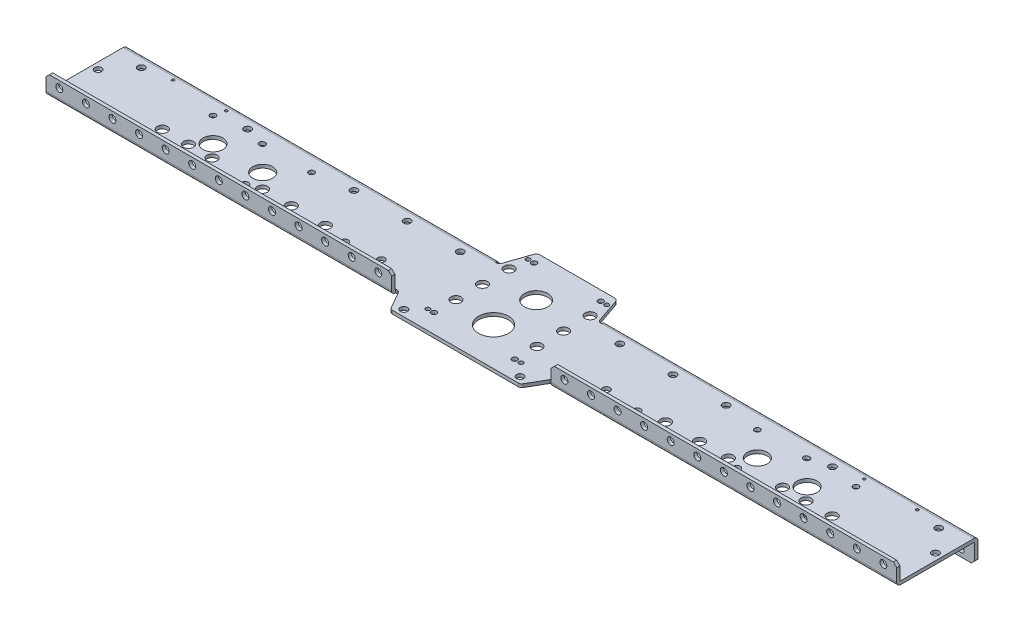
SolidWorks part; units mm, degrees
ref_plane "Front Plane" through (0, 0, 0) normal (0, 0, 1) x (1, 0, 0)
ref_plane "Top Plane" through (0, 0, 0) normal (0, 1, 0) x (1, 0, 0)
ref_plane "Right Plane" through (0, 0, 0) normal (1, 0, 0) x (0, 0, -1)
sketch "Sketch1" plane through (0, 0, 0) normal (0, 1, 0) x (1, 0, 0)
  line L32 (442.3147, 97.282) -> (370.4853, 97.282)
  line L33 (367.4833, 95.1407) -> (359.5123, 71.9913)
  line L34 (356.5103, 69.85) -> (355.6, 69.85)
  line L35 (355.6, 69.85) -> (0, 69.85)
  line L36 (0, 69.85) -> (0, 0)
  line L37 (0, 0) -> (330.2, 0)
  line L38 (330.2, 0) -> (331.5419, 0)
  line L39 (334.2915, -1.5875) -> (343.457, -17.4625)
  line L40 (346.2066, -19.05) -> (466.5934, -19.05)
  line L41 (469.343, -17.4625) -> (478.5085, -1.5875)
  line L42 (481.2581, 0) -> (482.6, 0)
  line L43 (482.6, 0) -> (812.8, 0)
  line L44 (812.8, 0) -> (812.8, 69.85)
  line L45 (812.8, 69.85) -> (457.2, 69.85)
  line L46 (457.2, 69.85) -> (456.2897, 69.85)
  line L47 (453.2877, 71.9913) -> (445.3167, 95.1407)
  circle A1 centre (806.45, 39.497) radius 3.3528
  arc A16 (445.3167, 95.1407) -> (442.3147, 97.282) centre (442.3147, 94.107) ccw
  arc A17 (370.4853, 97.282) -> (367.4833, 95.1407) centre (370.4853, 94.107) ccw
  arc A18 (356.5103, 69.85) -> (359.5123, 71.9913) centre (356.5103, 73.025) ccw
  arc A19 (334.2915, -1.5875) -> (331.5419, 0) centre (331.5419, -3.175) ccw
  arc A20 (343.457, -17.4625) -> (346.2066, -19.05) centre (346.2066, -15.875) ccw
  arc A21 (466.5934, -19.05) -> (469.343, -17.4625) centre (466.5934, -15.875) ccw
  arc A22 (481.2581, 0) -> (478.5085, -1.5875) centre (481.2581, -3.175) ccw
  arc A23 (453.2877, 71.9913) -> (456.2897, 69.85) centre (456.2897, 73.025) ccw
  circle A34 centre (641.35, 14.732) radius 3.3528
  circle A35 centre (642.7129, 33.02) radius 9.525
  arc A36 (666.4551, 53.7309) -> (666.4551, 59.0065) centre (666.8486, 56.3687) ccw
  arc A37 (666.4551, 7.0335) -> (666.4551, 12.3091) centre (666.8486, 9.6713) ccw
  circle A38 centre (678.9442, 20.828) radius 4.826
  circle A39 centre (711.2, 3.175) radius 1.27
  circle A40 centre (713.546, 9.6713) radius 2.667
  circle A41 centre (701.4504, 20.828) radius 4.826
  circle A42 centre (690.1973, 33.02) radius 9.525
  circle A43 centre (685.8, 61.722) radius 3.3528
  circle A44 centre (711.2, 66.675) radius 1.27
  circle A45 centre (713.546, 56.3687) radius 2.667
  circle A46 centre (726.4609, 20.828) radius 4.826
  circle A47 centre (762, 3.175) radius 1.27
  circle A48 centre (762, 66.675) radius 1.27
  circle A49 centre (787.4, 61.722) radius 3.3528
  circle A78 centre (350.8375, -12.8905) radius 3.4036
  circle A79 centre (361.9119, -1.0389) radius 2.032
  circle A80 centre (367.7539, -1.0389) radius 2.54
  circle A81 centre (367.6757, 20.066) radius 4.7625
  circle A82 centre (367.6757, 45.466) radius 4.7625
  circle A83 centre (367.6757, 70.866) radius 4.7625
  circle A84 centre (368.808, 87.8535) radius 2.032
  circle A85 centre (374.65, 87.8535) radius 2.54
  circle A86 centre (406.4, 57.9628) radius 11.1125
  circle A87 centre (406.4, 17.272) radius 14.2875
  circle A88 centre (461.9625, -12.8905) radius 3.4036
  circle A89 centre (445.0461, -1.0389) radius 2.54
  circle A90 centre (450.8881, -1.0389) radius 2.032
  circle A91 centre (445.1243, 20.066) radius 4.7625
  circle A92 centre (445.1243, 45.466) radius 4.7625
  circle A93 centre (438.15, 87.8535) radius 2.54
  circle A94 centre (443.992, 87.8535) radius 2.032
  circle A95 centre (445.1243, 70.866) radius 4.7625
  circle A96 centre (482.6, 61.722) radius 3.3528
  circle A97 centre (513.9255, 17.5473) radius 3.3528
  circle A98 centre (533.4, 61.722) radius 3.3528
  circle A99 centre (546.1, 14.732) radius 3.3528
  circle A100 centre (568.9249, 19.05) radius 4.826
  circle A101 centre (584.2, 61.722) radius 3.3528
  circle A102 centre (619.3642, 56.3687) radius 2.667
  circle A103 centre (601.4385, 19.05) radius 4.826
  circle A104 centre (619.3642, 9.6713) radius 2.667
  circle A105 centre (628.9477, 19.05) radius 4.826
  circle A125 centre (298.8745, 17.5473) radius 3.3528
  circle A126 centre (266.7, 14.732) radius 3.3528
  circle A127 centre (243.8751, 19.05) radius 4.826
  circle A128 centre (211.3615, 19.05) radius 4.826
  circle A129 centre (193.4358, 9.6713) radius 2.667
  circle A130 centre (183.8523, 19.05) radius 4.826
  circle A131 centre (170.0871, 33.02) radius 9.525
  circle A132 centre (171.45, 14.732) radius 3.3528
  arc A133 (146.3449, 7.0335) -> (146.3449, 12.3091) centre (146.7384, 9.6713) ccw
  circle A134 centre (133.8558, 20.828) radius 4.826
  circle A135 centre (122.6027, 33.02) radius 9.525
  circle A136 centre (99.254, 56.3687) radius 2.667
  circle A137 centre (101.6, 66.675) radius 1.27
  circle A138 centre (127, 61.722) radius 3.3528
  arc A139 (146.3449, 53.7309) -> (146.3449, 59.0065) centre (146.7384, 56.3687) ccw
  circle A140 centre (193.4358, 56.3687) radius 2.667
  circle A141 centre (228.6, 61.722) radius 3.3528
  circle A142 centre (279.4, 61.722) radius 3.3528
  circle A143 centre (330.2, 61.722) radius 3.3528
  circle A152 centre (50.8, 66.675) radius 1.27
  circle A153 centre (6.35, 39.497) radius 3.3528
  circle A154 centre (25.4, 61.722) radius 3.3528
  circle A155 centre (50.8, 3.175) radius 1.27
  circle A156 centre (101.6, 3.175) radius 1.27
  circle A157 centre (99.254, 9.6713) radius 2.667
  circle A158 centre (86.3391, 20.828) radius 4.826
  circle A159 centre (111.3496, 20.828) radius 4.826
  arc A161 (666.4551, 59.0065) -> (666.4551, 53.7309) centre (666.0616, 56.3687) ccw
  arc A163 (666.4551, 12.3091) -> (666.4551, 7.0335) centre (666.0616, 9.6713) ccw
  arc A165 (146.3449, 12.3091) -> (146.3449, 7.0335) centre (145.9514, 9.6713) ccw
  arc A167 (146.3449, 59.0065) -> (146.3449, 53.7309) centre (145.9514, 56.3687) ccw
extrude "Boss-Extrude1" add sketch "Sketch1" along normal blind 3.175 separate body
sketch "Sketch3" plane through (0, 0, 0) normal (-1, 0, 0) x (0, 0, 1)
  line L5 (-70.612, -15.875) -> (-70.612, -19.05)
  line L6 (-73.787, -19.05) -> (-70.612, -19.05)
  line L7 (-73.787, -15.875) -> (-73.787, -19.05)
  line L8 (-70.612, -0.762) -> (-70.612, -15.875)
  line L9 (-73.787, -0.762) -> (-73.787, -15.875)
  line L10 (-69.85, 0) -> (-69.85, 3.175)
  arc A2 (-69.85, 3.175) -> (-73.787, -0.762) centre (-69.85, -0.762) ccw
  arc A3 (-69.85, 0) -> (-70.612, -0.762) centre (-69.85, -0.762) ccw
extrude "Boss-Extrude2" add sketch "Sketch3" against normal blind 355.6
sketch "Sketch4" plane through (0, 0, -73.787) normal (0, 0, -1) x (-1, 0, 0)
  circle A14 centre (-342.9, -12.7) radius 2.667
  circle A15 centre (-317.5, -12.7) radius 2.667
  circle A16 centre (-292.1, -12.7) radius 2.667
  circle A17 centre (-266.7, -12.7) radius 2.667
  circle A18 centre (-241.3, -12.7) radius 2.667
  circle A19 centre (-215.9, -12.7) radius 2.667
  circle A20 centre (-190.5, -12.7) radius 2.667
  circle A21 centre (-165.1, -12.7) radius 2.667
  circle A22 centre (-139.7, -12.7) radius 2.667
  circle A23 centre (-114.3, -12.7) radius 2.667
  circle A24 centre (-88.9, -12.7) radius 2.667
  circle A25 centre (-63.5, -12.7) radius 2.667
  circle A26 centre (-38.1, -12.7) radius 2.667
  circle A27 centre (-12.7, -12.7) radius 2.667
extrude "Cut-Extrude1" cut sketch "Sketch4" against normal up to next
sketch "Sketch5" plane through (0, 0, 0) normal (-1, 0, 0) x (0, 0, 1)
  line L6 (3.937, 3.937) -> (3.937, 15.875)
  line L8 (3.937, 19.05) -> (3.937, 15.875)
  line L9 (0.762, 19.05) -> (3.937, 19.05)
  line L10 (0.762, 19.05) -> (0.762, 15.875)
  line L11 (0.762, 15.875) -> (0.762, 3.937)
  line L12 (0, 0) -> (0, 3.175)
  arc A2 (0, 0) -> (3.937, 3.937) centre (0, 3.937) ccw
  arc A3 (0, 3.175) -> (0.762, 3.937) centre (0, 3.937) ccw
sketch "Sketch6" plane through (812.8, 0, 0) normal (1, 0, 0) x (0, 0, -1)
  line L6 (73.787, -19.05) -> (73.787, -15.875)
  line L8 (73.787, -19.05) -> (70.612, -19.05)
  line L9 (70.612, -19.05) -> (70.612, -15.875)
  line L10 (70.612, -15.875) -> (70.612, -0.762)
  line L11 (73.787, -15.875) -> (73.787, -0.762)
  line L12 (69.85, 3.175) -> (69.85, 0)
  arc A2 (70.612, -0.762) -> (69.85, 0) centre (69.85, -0.762) ccw
  arc A3 (73.787, -0.762) -> (69.85, 3.175) centre (69.85, -0.762) ccw
extrude "Boss-Extrude3" add sketch "Sketch5" against normal blind 330.2
sketch "Sketch7" plane through (0, 0, 0.762) normal (0, 0, -1) x (-1, 0, 0)
  circle A5 centre (-12.7, 12.7) radius 3.3528
  circle A6 centre (-38.1, 12.7) radius 3.3528
  circle A7 centre (-63.5, 12.7) radius 3.3528
  circle A8 centre (-88.9, 12.7) radius 3.3528
  circle A9 centre (-114.3, 12.7) radius 3.3528
  circle A15 centre (-241.3, 12.7) radius 3.3528
  circle A16 centre (-215.9, 12.7) radius 3.3528
  circle A17 centre (-190.5, 12.7) radius 3.3528
  circle A18 centre (-165.1, 12.7) radius 3.3528
  circle A19 centre (-139.7, 12.7) radius 3.3528
  circle A23 centre (-317.5, 12.7) radius 3.3528
  circle A24 centre (-292.1, 12.7) radius 3.3528
  circle A25 centre (-266.7, 12.7) radius 3.3528
extrude "Cut-Extrude2" cut sketch "Sketch7" against normal up to next
extrude "Boss-Extrude4" add sketch "Sketch6" against normal blind 355.6
sketch "Sketch8" plane through (812.8, 0, 0) normal (1, 0, 0) x (0, 0, -1)
  line L6 (-0.762, 3.937) -> (-0.762, 15.875)
  line L7 (-0.762, 15.875) -> (-0.762, 19.05)
  line L8 (-3.937, 19.05) -> (-0.762, 19.05)
  line L9 (-3.937, 15.875) -> (-3.937, 19.05)
  line L10 (-3.937, 15.875) -> (-3.937, 3.937)
  line L11 (0, 3.175) -> (0, 0)
  arc A2 (-0.762, 3.937) -> (0, 3.175) centre (0, 3.937) ccw
  arc A3 (-3.937, 3.937) -> (0, 0) centre (0, 3.937) ccw
extrude "Boss-Extrude5" add sketch "Sketch8" against normal blind 330.2
chamfer "Chamfer1" distance 3.175 angle 45 8 edges at (355.6, -19.05, -72.1995) (0, -19.05, -72.1995) (330.2, 19.05, 2.3495) (0, 19.05, 2.3495) (482.6, 19.05, 2.3495) (457.2, -19.05, -72.1995) (812.8, -19.05, -72.1995) (812.8, 19.05, 2.3495)
sketch "Sketch9" plane through (0, 0, 3.937) normal (0, 0, 1) x (1, 0, 0)
  circle A5 centre (698.5, 12.7) radius 3.3528
  circle A6 centre (723.9, 12.7) radius 3.3528
  circle A7 centre (749.3, 12.7) radius 3.3528
  circle A8 centre (774.7, 12.7) radius 3.3528
  circle A9 centre (800.1, 12.7) radius 3.3528
  circle A12 centre (647.7, 12.7) radius 3.3528
  circle A13 centre (673.1, 12.7) radius 3.3528
  circle A17 centre (571.5, 12.7) radius 3.3528
  circle A18 centre (596.9, 12.7) radius 3.3528
  circle A19 centre (622.3, 12.7) radius 3.3528
  circle A23 centre (546.1, 12.7) radius 3.3528
  circle A24 centre (520.7, 12.7) radius 3.3528
  circle A25 centre (495.3, 12.7) radius 3.3528
extrude "Cut-Extrude3" cut sketch "Sketch9" against normal up to next
sketch "Sketch10" plane through (0, 0, -73.787) normal (0, 0, -1) x (-1, 0, 0)
  circle A5 centre (-698.5, -12.7) radius 2.667
  circle A6 centre (-723.9, -12.7) radius 2.667
  circle A7 centre (-749.3, -12.7) radius 2.667
  circle A8 centre (-774.7, -12.7) radius 2.667
  circle A9 centre (-800.1, -12.7) radius 2.667
  circle A12 centre (-647.7, -12.7) radius 2.667
  circle A13 centre (-673.1, -12.7) radius 2.667
  circle A15 centre (-622.3, -12.7) radius 2.667
  circle A17 centre (-596.9, -12.7) radius 2.667
  circle A19 centre (-571.5, -12.7) radius 2.667
  circle A21 centre (-546.1, -12.7) radius 2.667
  circle A23 centre (-520.7, -12.7) radius 2.667
  circle A26 centre (-469.9, -12.7) radius 2.667
  circle A27 centre (-495.3, -12.7) radius 2.667
extrude "Cut-Extrude4" cut sketch "Sketch10" against normal up to next
